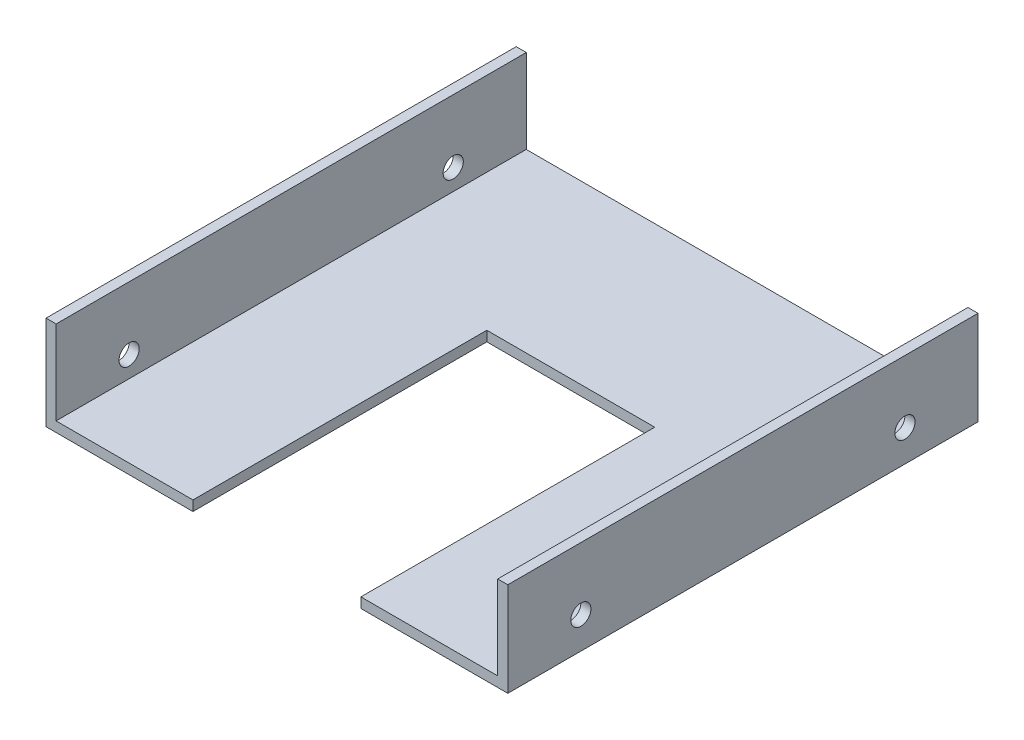
SolidWorks part; units mm, degrees
ref_plane "Front Plane" through (0, 0, 0) normal (0, 0, 1) x (1, 0, 0)
ref_plane "Top Plane" through (0, 0, 0) normal (0, 1, 0) x (1, 0, 0)
ref_plane "Right Plane" through (0, 0, 0) normal (1, 0, 0) x (0, 0, -1)
sketch "Sketch1" plane through (0, 0, 0) normal (0, 1, 0) x (1, 0, 0)
  line L1 (-8.0172, -204.9266) -> (-8.0172, -238.1306) construction
  line L2 (-95.5172, 41.8694) -> (179.4828, 41.8694)
  line L3 (-95.5172, 41.8694) -> (-95.5172, -238.1306)
  line L4 (-95.5172, -238.1306) -> (179.4828, -238.1306)
  line L5 (179.4828, 41.8694) -> (179.4828, -238.1306)
  line L6 (-8.0172, -238.1306) -> (-8.0172, -63.1306)
  line L7 (-8.0172, -63.1306) -> (91.9828, -63.1306)
  line L8 (91.9828, -63.1306) -> (91.9828, -238.1306)
extrude "Boss-Extrude3" add sketch "Sketch1" along normal blind 6 contours L7 L8 L4 L5 L2 L3 L6
sketch "Sketch2" plane through (0, 6, 0) normal (0, 1, 0) x (1, 0, 0)
  line L0 (-95.5172, -17.1062) -> (-89.5172, -17.1062) construction
  line L2 (-95.5172, 41.8694) -> (-95.5172, -238.1306) construction
  line L3 (-89.5172, -17.1062) -> (-89.5172, -238.1306)
  line L4 (-95.5172, -238.1306) -> (-8.0172, -238.1306) construction
  line L5 (-89.5172, -17.1062) -> (-89.5172, 41.8694)
  line L6 (-95.5172, 41.8694) -> (179.4828, 41.8694) construction
  line L15 (-8.0172, -63.1306) -> (91.9828, -63.1306)
  line L16 (91.9828, -63.1306) -> (91.9828, -238.1306)
  line L17 (91.9828, -238.1306) -> (179.4828, -238.1306)
  line L18 (179.4828, -238.1306) -> (179.4828, 41.8694)
  line L19 (179.4828, 41.8694) -> (-95.5172, 41.8694)
  line L20 (-95.5172, 41.8694) -> (-95.5172, -238.1306)
  line L21 (-95.5172, -238.1306) -> (-8.0172, -238.1306)
  line L22 (-8.0172, -238.1306) -> (-8.0172, -63.1306)
  line L27 (-89.5172, 41.8694) -> (-95.5172, 41.8694)
  line L28 (-95.5172, 41.8694) -> (-95.5172, -238.1306)
  line L29 (-95.5172, -238.1306) -> (-89.5172, -238.1306)
  dimension "D1" = 0
extrude "Boss-Extrude5" add sketch "Sketch2" along normal blind 50
sketch "Sketch3" plane through (0, 6, 0) normal (0, 1, 0) x (1, 0, 0)
  line L2 (173.4828, -39.3635) -> (173.4828, -238.1306)
  line L3 (91.9828, -238.1306) -> (179.4828, -238.1306) construction
  line L4 (173.4828, -39.3635) -> (173.4828, 41.8694)
  line L5 (-89.5172, 41.8694) -> (179.4828, 41.8694) construction
  line L13 (-89.5172, 41.8694) -> (-89.5172, -238.1306)
  line L14 (-89.5172, -238.1306) -> (-8.0172, -238.1306)
  line L15 (-8.0172, -238.1306) -> (-8.0172, -63.1306)
  line L16 (-8.0172, -63.1306) -> (91.9828, -63.1306)
  line L17 (91.9828, -63.1306) -> (91.9828, -238.1306)
  line L18 (91.9828, -238.1306) -> (179.4828, -238.1306)
  line L19 (179.4828, -238.1306) -> (179.4828, 41.8694)
  line L20 (179.4828, 41.8694) -> (-89.5172, 41.8694)
  line L26 (173.4828, -238.1306) -> (179.4828, -238.1306)
  line L27 (179.4828, -238.1306) -> (179.4828, 41.8694)
  line L28 (179.4828, 41.8694) -> (173.4828, 41.8694)
  dimension "D1" = 0
extrude "Boss-Extrude6" add sketch "Sketch3" along normal blind 50
sketch "Sketch4" plane through (179.4828, 0, 0) normal (1, 0, 0) x (0, 0, -1)
  line L0 (-213.1306, 0) -> (-213.1306, 6.3282) construction
  line L1 (41.8694, 0) -> (-238.1306, 0) construction
  line L2 (-213.1306, 6.3282) -> (41.8694, 6.3282) construction
  line L3 (41.8694, 56) -> (41.8694, 0) construction
  line L4 (-213.1306, 6.3282) -> (-241.666, 6.3282) construction
  line L5 (-238.1306, 24.8282) -> (-213.1306, 24.8282) construction
  line L6 (-238.1306, 56) -> (-238.1306, 0) construction
  line L7 (-213.1306, 24.8282) -> (-213.1306, 6.3282) construction
  line L8 (-213.1306, 24.8282) -> (-194.6306, 24.8282) construction
  line L10 (41.8694, 24.8282) -> (16.8694, 24.8282) construction
  line L11 (16.8694, 24.8282) -> (-1.6306, 24.8282) construction
  line L12 (16.8694, 24.8282) -> (16.8694, 6.3282) construction
  circle A0 centre (-194.6306, 24.8282) radius 18.5
  circle A1 centre (-194.6306, 18.8282) radius 6
  circle A2 centre (-1.6306, 24.8282) radius 18.5
  circle A3 centre (-1.6306, 18.8282) radius 6
  dimension "D1" = 25
  dimension "D2" = 18.5
  dimension "D3" = 18.5
  dimension "D5" = 18.5
  dimension "D6" = 25
extrude "Cut-Extrude1" cut sketch "Sketch4" against normal blind 6 contours A1 | A3
sketch "Sketch5" plane through (-95.5172, 0, 0) normal (-1, 0, 0) x (0, 0, 1)
  line L0 (-16.9589, 0) -> (-16.9589, 6) construction
  line L1 (-41.8694, 0) -> (238.1306, 0) construction
  line L2 (-41.8694, 6) -> (238.1306, 6) construction
  line L3 (-41.8694, 24.5) -> (-16.8694, 24.5) construction
  line L4 (-41.8694, 56) -> (-41.8694, 0) construction
  line L5 (-16.8694, 24.5) -> (-16.8694, 6) construction
  line L6 (-16.8694, 24.5) -> (1.6306, 24.5) construction
  line L7 (1.6306, 24.5) -> (1.6306, -12.0246) construction
  line L8 (238.1306, 24.5) -> (213.1306, 24.5) construction
  line L9 (238.1306, 56) -> (238.1306, 0) construction
  line L10 (213.1306, 24.5) -> (213.1306, 6) construction
  line L11 (213.1306, 24.5) -> (194.6306, 24.5) construction
  line L12 (194.6306, 24.5) -> (194.6306, -24.4095) construction
  circle A0 centre (1.6306, 24.5) radius 18.5
  circle A1 centre (1.6306, 18.5) radius 6
  circle A2 centre (194.6306, 24.5) radius 18.5
  circle A3 centre (194.6306, 18.5) radius 6
  dimension "D4" = 12
  dimension "D7" = 12
  dimension "D1" = 18.5
  dimension "D2" = 18.5
  dimension "D3" = 25
  dimension "D5" = 25
  dimension "D6" = 18.5
extrude "Cut-Extrude2" cut sketch "Sketch5" against normal blind 6 contours A1 | A3
